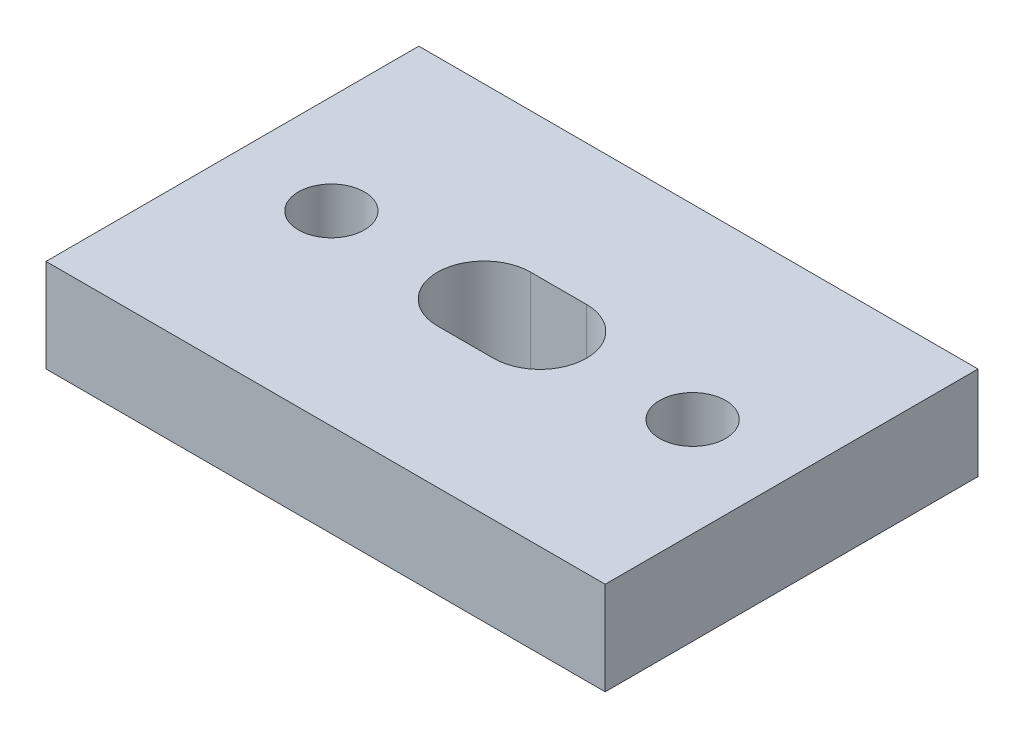
SolidWorks part; units mm, degrees
ref_plane "Front Plane" through (0, 0, 0) normal (0, 0, 1) x (1, 0, 0)
ref_plane "Top Plane" through (0, 0, 0) normal (0, 1, 0) x (1, 0, 0)
ref_plane "Right Plane" through (0, 0, 0) normal (1, 0, 0) x (0, 0, -1)
sketch "Sketch1" plane through (0, 0, 0) normal (0, 1, 0) x (1, 0, 0)
  line L0 (-19.05, 0) -> (19.05, 0) construction
  line L1 (-19.05, 12.7) -> (19.05, 12.7)
  line L2 (-19.05, 12.7) -> (-19.05, -12.7)
  line L3 (-19.05, -12.7) -> (19.05, -12.7)
  line L4 (19.05, 12.7) -> (19.05, -12.7)
  line L5 (-19.05, 12.7) -> (19.05, -12.7) construction
  line L6 (-19.05, -12.7) -> (19.05, 12.7) construction
  line L7 (-1.905, 0) -> (1.905, 0) construction
  line L8 (-1.905, 3.175) -> (1.905, 3.175)
  line L9 (-1.905, -3.175) -> (1.905, -3.175)
  circle A1 centre (-12.3063, 0) radius 2.2479
  circle A2 centre (12.3063, 0) radius 2.2479
  arc A3 (-1.905, 3.175) -> (-1.905, -3.175) centre (-1.905, 0) ccw
  arc A4 (1.905, -3.175) -> (1.905, 3.175) centre (1.905, 0) ccw
  point P0 (0, 0)
  point P14 (0, 0)
  point P19 (0, 0)
  point P20 (-5.08, 0)
  point P21 (5.08, 0)
  point P22 (0, 0)
  dimension "D1" = 6.35
  dimension "D4" = 4.4958
  dimension "D5" = 4.4958
  dimension "D2" = 38.1
  dimension "D3" = 25.4
  dimension "D6" = 6.7437
  dimension "D7" = 6.7437
  dimension "D8" = 10.16
  dimension "D10" = 3.81
extrude "Boss-Extrude1" add sketch "Sketch1" along normal blind 6.35
